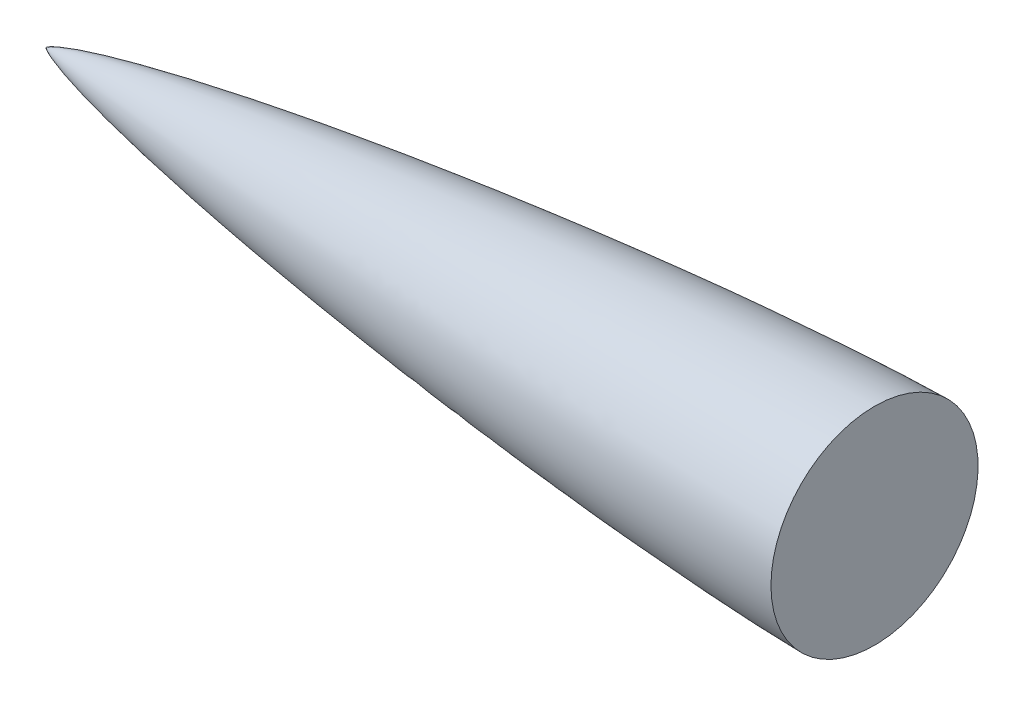
SolidWorks part; units mm, degrees
ref_plane "Front Plane" through (0, 0, 0) normal (0, 0, 1) x (1, 0, 0)
ref_plane "Top Plane" through (0, 0, 0) normal (0, 1, 0) x (1, 0, 0)
ref_plane "Right Plane" through (0, 0, 0) normal (1, 0, 0) x (0, 0, -1)
sketch "Sketch11" plane through (0, 0, 0) normal (0, 0, 1) x (1, 0, 0)
  line L0 (0, 0) -> (24, 0)
  line L1 (24, 0) -> (24, 3)
  spline S0 degree 4 poles (0, 0) (0.0021, 0.0036) (0.007, 0.0095) (0.0161, 0.0165) (0.0294, 0.0259) (0.0463, 0.0362) (0.0718, 0.0504) (0.115, 0.0717) (0.1906, 0.1049) (0.3284, 0.1579) (0.581, 0.2421) (1.0067, 0.3642) (1.7626, 0.5521) (2.8209, 0.7773) (4.1242, 1.0213) (5.606, 1.2689) (7.0912, 1.4949) (8.579, 1.703) (10.0689, 1.8956) (11.5606, 2.0741) (13.0538, 2.2393) (14.5483, 2.3917) (16.0441, 2.5314) (17.5411, 2.6578) (19.0392, 2.7704) (20.5384, 2.8673) (21.9659, 2.9427) (23.0191, 2.9823) (23.6973, 2.9982) (24, 3) knots 0 0 0 0 0 0.000683 0.001272 0.001867 0.002703 0.003938 0.006082 0.009808 0.016327 0.028282 0.049986 0.082826 0.144772 0.206717 0.268663 0.330609 0.392555 0.4545 0.516446 0.578392 0.640337 0.702283 0.764229 0.826175 0.88812 0.950066 1 1 1 1 1 construction
  spline S1 degree 4 poles (0, 0) (0.0021, 0.0036) (0.007, 0.0095) (0.0161, 0.0165) (0.0294, 0.0259) (0.0463, 0.0362) (0.0718, 0.0504) (0.115, 0.0717) (0.1906, 0.1049) (0.3284, 0.1579) (0.581, 0.2421) (1.0067, 0.3642) (1.7626, 0.5521) (2.8209, 0.7773) (4.1242, 1.0213) (5.606, 1.2689) (7.0912, 1.4949) (8.579, 1.703) (10.0689, 1.8956) (11.5606, 2.0741) (13.0538, 2.2393) (14.5483, 2.3917) (16.0441, 2.5314) (17.5411, 2.6578) (19.0392, 2.7704) (20.5384, 2.8673) (21.9659, 2.9427) (23.0191, 2.9823) (23.6973, 2.9982) (24, 3) knots 0 0 0 0 0 0.000683 0.001272 0.001867 0.002703 0.003938 0.006082 0.009808 0.016327 0.028282 0.049986 0.082826 0.144772 0.206717 0.268663 0.330609 0.392555 0.4545 0.516446 0.578392 0.640337 0.702283 0.764229 0.826175 0.88812 0.950066 1 1 1 1 1
  dimension "D1" = 24
revolve "Revolve10" add sketch "Sketch11" angle 360 about L0
